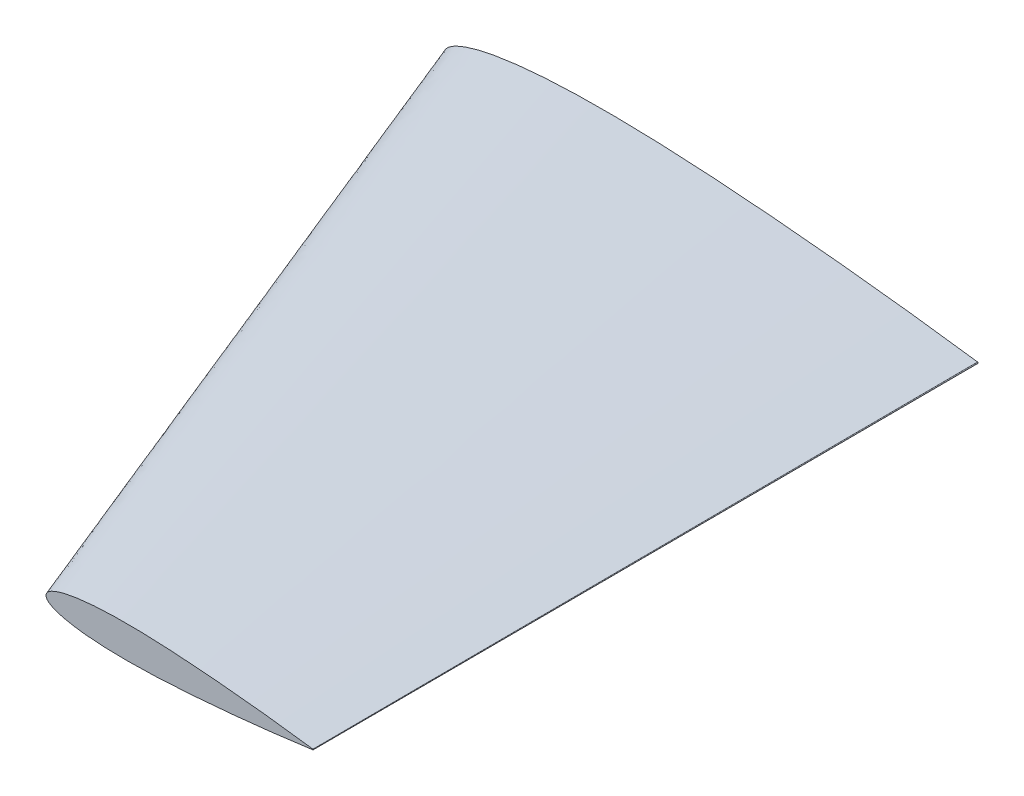
SolidWorks part; units mm, degrees
ref_plane "Front Plane" through (0, 0, 0) normal (0, 0, 1) x (1, 0, 0)
ref_plane "Top Plane" through (0, 0, 0) normal (0, 1, 0) x (1, 0, 0)
ref_plane "Right Plane" through (0, 0, 0) normal (1, 0, 0) x (0, 0, -1)
sketch "Sketch2" plane through (0, 0, 0) normal (0, 0, 1) x (1, 0, 0)
  arc A0 (203.2, 0.256) -> (203.2, -0.256) centre (203.1165, 0) cw
  spline S1 degree 3 poles (203.2, 0.256) (203.1604, 0.2616) (203.0024, 0.2838) (202.3715, 0.372) (201.427, 0.5039) (200.1709, 0.6771) (198.8821, 0.8543) (197.366, 1.0608) (195.6262, 1.2952) (193.6669, 1.5566) (191.4925, 1.843) (189.1083, 2.1532) (186.5196, 2.4846) (182.6777, 2.9695) (178.5842, 3.4727) (174.2487, 3.9917) (170.7379, 4.4039) (167.0654, 4.8259) (163.2402, 5.2565) (159.271, 5.6927) (155.1671, 6.1332) (150.9381, 6.5751) (146.5939, 7.0173) (142.1445, 7.4566) (137.6006, 7.8915) (132.9725, 8.3191) (128.2711, 8.7378) (123.5074, 9.1443) (118.6925, 9.5368) (113.8378, 9.9127) (108.9544, 10.269) (104.0539, 10.6035) (99.1477, 10.9136) (92.6287, 11.2894) (86.139, 11.6065) (78.1265, 11.915) (71.8185, 12.0888) (65.6005, 12.1791) (61.0562, 12.2029) (56.6065, 12.1819) (52.262, 12.115) (48.0326, 12.0004) (43.9283, 11.8384) (39.9587, 11.628) (36.1328, 11.3696) (32.4599, 11.0635) (28.9483, 10.71) (25.6063, 10.3106) (22.4415, 9.867) (19.4615, 9.3798) (16.673, 8.8516) (14.0825, 8.2843) (11.696, 7.6799) (9.5188, 7.041) (7.5557, 6.3699) (5.8109, 5.6687) (4.2878, 4.9396) (2.9893, 4.184) (1.917, 3.4033) (1.0729, 2.5961) (0.4591, 1.7602) (0.0838, 0.8914) (-0.0408, 0) (0.0838, -0.8914) (0.4591, -1.7602) (1.0729, -2.5961) (1.917, -3.4033) (2.9893, -4.184) (4.2878, -4.9396) (5.8109, -5.6687) (7.5557, -6.3699) (9.5188, -7.041) (11.696, -7.6799) (14.0825, -8.2843) (16.673, -8.8516) (19.4615, -9.3798) (22.4415, -9.867) (25.6063, -10.3106) (28.9483, -10.71) (32.4599, -11.0635) (36.1328, -11.3696) (39.9587, -11.628) (43.9283, -11.8384) (48.0326, -12.0004) (52.262, -12.115) (56.6065, -12.1819) (61.0562, -12.2029) (65.6005, -12.1791) (71.8185, -12.0888) (79.7471, -11.8704) (87.7586, -11.532) (94.2472, -11.1961) (99.1477, -10.9136) (104.0539, -10.6035) (108.9544, -10.269) (113.8378, -9.9127) (118.6925, -9.5368) (123.5074, -9.1443) (128.2711, -8.7378) (132.9725, -8.3191) (137.6006, -7.8915) (142.1445, -7.4566) (146.5939, -7.0173) (150.9381, -6.5751) (155.1671, -6.1332) (159.271, -5.6927) (163.2402, -5.2565) (167.0654, -4.8259) (170.7379, -4.4039) (174.2487, -3.9917) (178.5842, -3.4727) (182.6777, -2.9695) (186.5196, -2.4846) (189.1083, -2.1532) (191.4925, -1.843) (193.6669, -1.5566) (195.6262, -1.2952) (197.366, -1.0608) (198.8821, -0.8543) (200.1709, -0.6771) (201.427, -0.5039) (202.3715, -0.372) (203.0024, -0.2838) (203.1604, -0.2616) (203.2, -0.256) knots 0 0 0 0 0.000289 0.001156 0.004612 0.007194 0.010336 0.014031 0.018272 0.023046 0.028343 0.03415 0.040454 0.047238 0.062187 0.070314 0.078852 0.08778 0.097078 0.106722 0.116691 0.126961 0.137507 0.148306 0.159331 0.170556 0.181957 0.193504 0.205171 0.216932 0.228758 0.240621 0.252495 0.26435 0.287898 0.299536 0.322405 0.333584 0.344559 0.355306 0.3658 0.376018 0.385937 0.395538 0.404798 0.413699 0.422221 0.430349 0.438066 0.445357 0.452209 0.458612 0.464554 0.47003 0.475035 0.479569 0.483637 0.48725 0.490431 0.493219 0.495674 0.497891 0.5 0.502109 0.504326 0.506781 0.509569 0.51275 0.516363 0.520431 0.524965 0.52997 0.535446 0.541388 0.547791 0.554643 0.561934 0.569651 0.577779 0.586301 0.595202 0.604462 0.614063 0.623982 0.6342 0.644694 0.655441 0.666416 0.677595 0.700464 0.723839 0.73565 0.747505 0.759379 0.771242 0.783068 0.794829 0.806496 0.818043 0.829444 0.840669 0.851694 0.862493 0.873039 0.883309 0.893278 0.902922 0.91222 0.921148 0.929686 0.937813 0.952762 0.959546 0.96585 0.971657 0.976954 0.981728 0.985969 0.989664 0.992806 0.995388 0.998844 0.999711 1 1 1 1
ref_plane "Plane1" through (0, 0, 254) normal (0, 0, 1) x (1, 0, 0)
sketch "Sketch3" plane through (0, 0, 254) normal (0, 0, 1) x (1, 0, 0)
  arc A0 (204.216, 0.128) -> (204.216, -0.128) centre (204.1984, 0) cw
  spline S1 degree 3 poles (204.216, 0.128) (204.1962, 0.1308) (204.1172, 0.1419) (203.8017, 0.186) (203.3295, 0.252) (202.7015, 0.3386) (202.0571, 0.4272) (201.299, 0.5304) (200.4291, 0.6476) (199.4494, 0.7783) (198.3623, 0.9215) (197.1701, 1.0766) (195.8758, 1.2423) (193.9548, 1.4847) (191.9081, 1.7363) (189.7404, 1.9959) (187.9849, 2.202) (186.1487, 2.4129) (184.2361, 2.6282) (182.2515, 2.8463) (180.1996, 3.0666) (178.0851, 3.2875) (175.9129, 3.5087) (173.6883, 3.7283) (171.4163, 3.9458) (169.1022, 4.1595) (166.7515, 4.3689) (164.3697, 4.5722) (161.9623, 4.7684) (159.5349, 4.9564) (157.0932, 5.1345) (154.643, 5.3018) (152.1899, 5.4568) (148.9303, 5.6447) (145.6855, 5.8032) (141.6792, 5.9575) (138.5253, 6.0444) (135.4162, 6.0896) (133.1441, 6.1015) (130.9193, 6.0909) (128.747, 6.0575) (126.6323, 6.0002) (124.5802, 5.9192) (122.5953, 5.814) (120.6824, 5.6848) (118.8459, 5.5317) (117.0901, 5.355) (115.4191, 5.1553) (113.8368, 4.9335) (112.3467, 4.6899) (110.9525, 4.4258) (109.6572, 4.1422) (108.464, 3.8399) (107.3754, 3.5205) (106.3938, 3.1849) (105.5214, 2.8344) (104.7599, 2.4698) (104.1107, 2.092) (103.5745, 1.7016) (103.1525, 1.298) (102.8455, 0.8801) (102.6579, 0.4457) (102.5956, 0) (102.6579, -0.4457) (102.8455, -0.8801) (103.1525, -1.298) (103.5745, -1.7016) (104.1107, -2.092) (104.7599, -2.4698) (105.5214, -2.8344) (106.3938, -3.1849) (107.3754, -3.5205) (108.464, -3.8399) (109.6572, -4.1422) (110.9525, -4.4258) (112.3467, -4.6899) (113.8368, -4.9335) (115.4191, -5.1553) (117.0901, -5.355) (118.8459, -5.5317) (120.6824, -5.6848) (122.5953, -5.814) (124.5802, -5.9192) (126.6323, -6.0002) (128.747, -6.0575) (130.9193, -6.0909) (133.1441, -6.1015) (135.4162, -6.0896) (138.5253, -6.0444) (142.4895, -5.9352) (146.4953, -5.766) (149.7396, -5.598) (152.1899, -5.4568) (154.643, -5.3018) (157.0932, -5.1345) (159.5349, -4.9564) (161.9623, -4.7684) (164.3697, -4.5722) (166.7515, -4.3689) (169.1022, -4.1595) (171.4163, -3.9458) (173.6883, -3.7283) (175.9129, -3.5087) (178.0851, -3.2875) (180.1996, -3.0666) (182.2515, -2.8463) (184.2361, -2.6282) (186.1487, -2.4129) (187.9849, -2.202) (189.7404, -1.9959) (191.9081, -1.7363) (193.9548, -1.4847) (195.8758, -1.2423) (197.1701, -1.0766) (198.3623, -0.9215) (199.4494, -0.7783) (200.4291, -0.6476) (201.299, -0.5304) (202.0571, -0.4272) (202.7015, -0.3386) (203.3295, -0.252) (203.8017, -0.186) (204.1172, -0.1419) (204.1962, -0.1308) (204.216, -0.128) knots 0 0 0 0 0.000289 0.001156 0.004612 0.007194 0.010336 0.014031 0.018272 0.023046 0.028343 0.03415 0.040454 0.047238 0.062187 0.070314 0.078852 0.08778 0.097078 0.106722 0.116691 0.126961 0.137507 0.148306 0.159331 0.170556 0.181957 0.193504 0.205171 0.216932 0.228758 0.240621 0.252495 0.26435 0.287898 0.299536 0.322405 0.333584 0.344559 0.355306 0.3658 0.376018 0.385937 0.395538 0.404798 0.413699 0.422221 0.430349 0.438066 0.445357 0.452209 0.458612 0.464554 0.47003 0.475035 0.479569 0.483637 0.48725 0.490431 0.493219 0.495674 0.497891 0.5 0.502109 0.504326 0.506781 0.509569 0.51275 0.516363 0.520431 0.524965 0.52997 0.535446 0.541388 0.547791 0.554643 0.561934 0.569651 0.577779 0.586301 0.595202 0.604462 0.614063 0.623982 0.6342 0.644694 0.655441 0.666416 0.677595 0.700464 0.723839 0.73565 0.747505 0.759379 0.771242 0.783068 0.794829 0.806496 0.818043 0.829444 0.840669 0.851694 0.862493 0.873039 0.883309 0.893278 0.902922 0.91222 0.921148 0.929686 0.937813 0.952762 0.959546 0.96585 0.971657 0.976954 0.981728 0.985969 0.989664 0.992806 0.995388 0.998844 0.999711 1 1 1 1
  point P0 (102.616, 0)
  point P4 (102.616, 0)
loft "Loft1" add profiles "Sketch2", "Sketch3"
